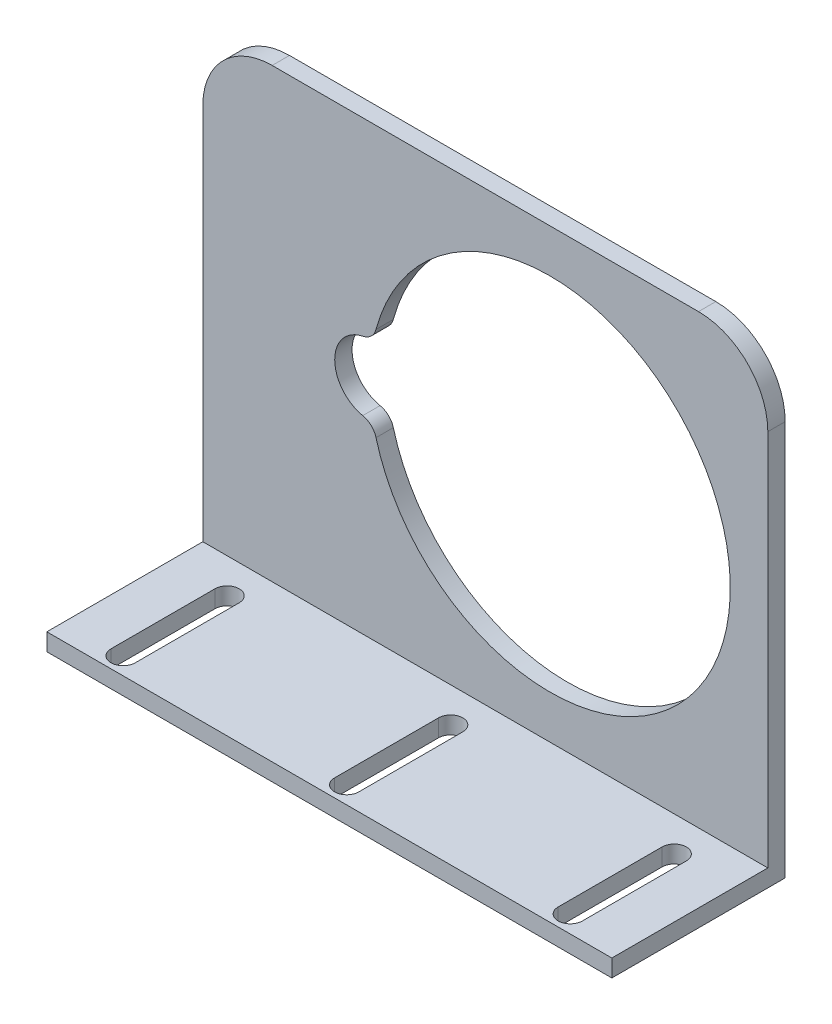
SolidWorks part; units mm, degrees
ref_plane "Front Plane" through (0, 0, 0) normal (0, 0, 1) x (1, 0, 0)
ref_plane "Top Plane" through (0, 0, 0) normal (0, 1, 0) x (1, 0, 0)
ref_plane "Right Plane" through (0, 0, 0) normal (1, 0, 0) x (0, 0, -1)
sketch "Sketch1" plane through (0, 0, 0) normal (0, 1, 0) x (1, 0, 0)
  line L1 (-81.5, 25) -> (81.5, 25)
  line L2 (-81.5, 25) -> (-81.5, -25)
  line L3 (-81.5, -25) -> (81.5, -25)
  line L4 (81.5, 25) -> (81.5, -25)
  line L5 (-81.5, 25) -> (81.5, -25) construction
  line L6 (-81.5, -25) -> (81.5, 25) construction
  point P0 (0, 0)
  dimension "D1" = 50
  dimension "D2" = 163
extrude "Boss-Extrude1" add sketch "Sketch1" along normal blind 5
sketch "Sketch6" plane through (0, 5, 0) normal (0, 1, 0) x (1, 0, 0)
  line L0 (81.5, -25) -> (81.5, 25) construction
  line L1 (-81.5, 25) -> (81.5, 25)
  line L2 (-81.5, 25) -> (-81.5, 20)
  line L3 (-81.5, 20) -> (81.5, 20)
  line L4 (81.5, 25) -> (81.5, 20)
  dimension "D1" = 5
extrude "Boss-Extrude2" add sketch "Sketch6" along normal blind 129
sketch "Sketch7" plane through (0, 0, -20) normal (0, 0, 1) x (1, 0, 0)
  line L0 (-81.5, 5) -> (81.5, 5) construction
  arc A0 (-32.3397, 59.4216) -> (-32.3397, 79.5784) centre (18.6743, 69.5) ccw
  arc A1 (-32.3397, 79.5784) -> (-32.3397, 59.4216) centre (-33.3257, 69.5) ccw
  dimension "D1" = 104
  dimension "D2" = 64.5
extrude "Cut-Extrude1" cut sketch "Sketch7" against normal through all
fillet "Fillet1" radius 5 2 edges at (-32.3397, 79.5784, -22.5) (-32.3397, 59.4216, -22.5)
fillet "Fillet2" radius 20 2 edges at (-81.5, 134, -22.5) (81.5, 134, -22.5)
sketch "Sketch9" plane through (0, 5, 0) normal (0, 1, 0) x (1, 0, 0)
  line L0 (-64.5, 10) -> (-64.5, -20) construction
  line L1 (-61, 10) -> (-61, -20)
  line L2 (-68, 10) -> (-68, -20)
  line L3 (-81.5, -25) -> (81.5, -25) construction
  line L4 (-81.5, 20) -> (-81.5, -25) construction
  arc A0 (-61, 10) -> (-68, 10) centre (-64.5, 10) ccw
  arc A1 (-68, -20) -> (-61, -20) centre (-64.5, -20) ccw
  point P2 (-64.5, -5)
  point P9 (-64.5, -23.5)
  dimension "D1" = 30
  dimension "D2" = 7
  dimension "D3" = 20
  dimension "D4" = 17
extrude "Cut-Extrude2" cut sketch "Sketch9" against normal through all
mirror "Mirror3" about plane through (0, 0, 0) normal (1, 0, 0) of "Cut-Extrude2"
sketch "Sketch10" plane through (0, 5, 0) normal (0, 1, 0) x (1, 0, 0)
  line L0 (0, 10) -> (0, -20) construction
  line L1 (3.5, 10) -> (3.5, -20)
  line L2 (-3.5, 10) -> (-3.5, -20)
  line L3 (-81.5, -25) -> (81.5, -25) construction
  arc A0 (3.5, 10) -> (-3.5, 10) centre (0, 10) ccw
  arc A1 (-3.5, -20) -> (3.5, -20) centre (0, -20) ccw
  point P3 (0, -5)
  point P10 (0, -25)
  dimension "D1" = 30
  dimension "D2" = 7
  dimension "D3" = 20
extrude "Cut-Extrude3" cut sketch "Sketch10" against normal through all
